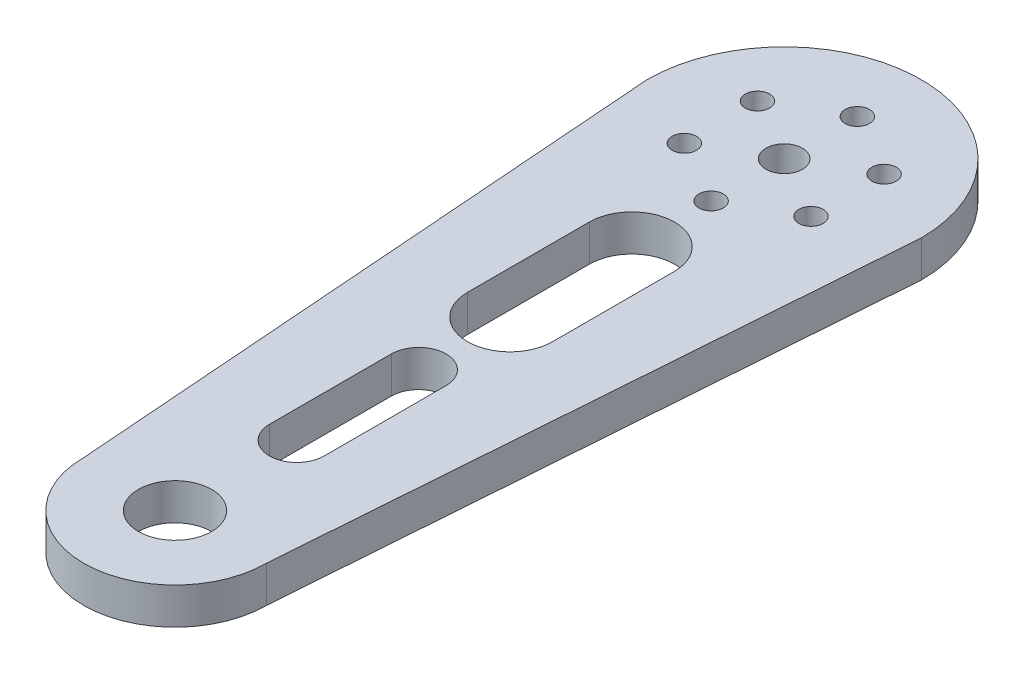
SolidWorks part; units mm, degrees
ref_plane "Front Plane" through (0, 0, 0) normal (0, 0, 1) x (1, 0, 0)
ref_plane "Top Plane" through (0, 0, 0) normal (0, 1, 0) x (1, 0, 0)
ref_plane "Right Plane" through (0, 0, 0) normal (1, 0, 0) x (0, 0, -1)
sketch "草图1" plane through (0, 0, 0) normal (0, 1, 0) x (1, 0, 0)
  line L0 (0, 0) -> (0, -100) construction
  line L1 (15, -100) -> (22.5, 0)
  line L2 (-15, -100) -> (-22.5, 0)
  arc A0 (22.5, 0) -> (-22.5, 0) centre (0, 0) ccw
  circle A1 centre (0, 0) radius 12 construction
  circle A2 centre (0, 12) radius 2
  circle A3 centre (10.3923, 6) radius 2
  circle A4 centre (10.3923, -6) radius 2
  circle A5 centre (0, -12) radius 2
  circle A6 centre (-10.3923, -6) radius 2
  circle A7 centre (-10.3923, 6) radius 2
  circle A8 centre (0, 0) radius 3
  arc A9 (-15, -100) -> (15, -100) centre (0, -100) ccw
  circle A10 centre (0, -100) radius 6
  point P18 (0, 0)
  dimension "D1" = 45
  dimension "D2" = 24
  dimension "D3" = 2
  dimension "D5" = 6
  dimension "D7" = 30
  dimension "D8" = 12
  dimension "D6" = 100
  dimension "D4" = 6
extrude "凸台-拉伸1" add sketch "草图1" along normal blind 6
sketch "草图2" plane through (0, 6, 0) normal (0, 1, 0) x (1, 0, 0)
  line L1 (0, -80) -> (0, -60) construction
  line L6 (-4.5, -80) -> (-4.5, -60)
  line L7 (4.5, -80) -> (4.5, -60)
  line L9 (0, -45) -> (0, -25) construction
  line L11 (-7, -45) -> (-7, -25)
  line L12 (7, -45) -> (7, -25)
  arc A0 (-4.5, -80) -> (4.5, -80) centre (0, -80) ccw
  arc A1 (4.5, -60) -> (-4.5, -60) centre (0, -60) ccw
  arc A2 (-7, -45) -> (7, -45) centre (0, -45) ccw
  arc A3 (7, -25) -> (-7, -25) centre (0, -25) ccw
  point P6 (0, -70)
  point P15 (0, -35)
  dimension "D1" = 20
extrude "切除-拉伸1" cut sketch "草图2" against normal blind 10
